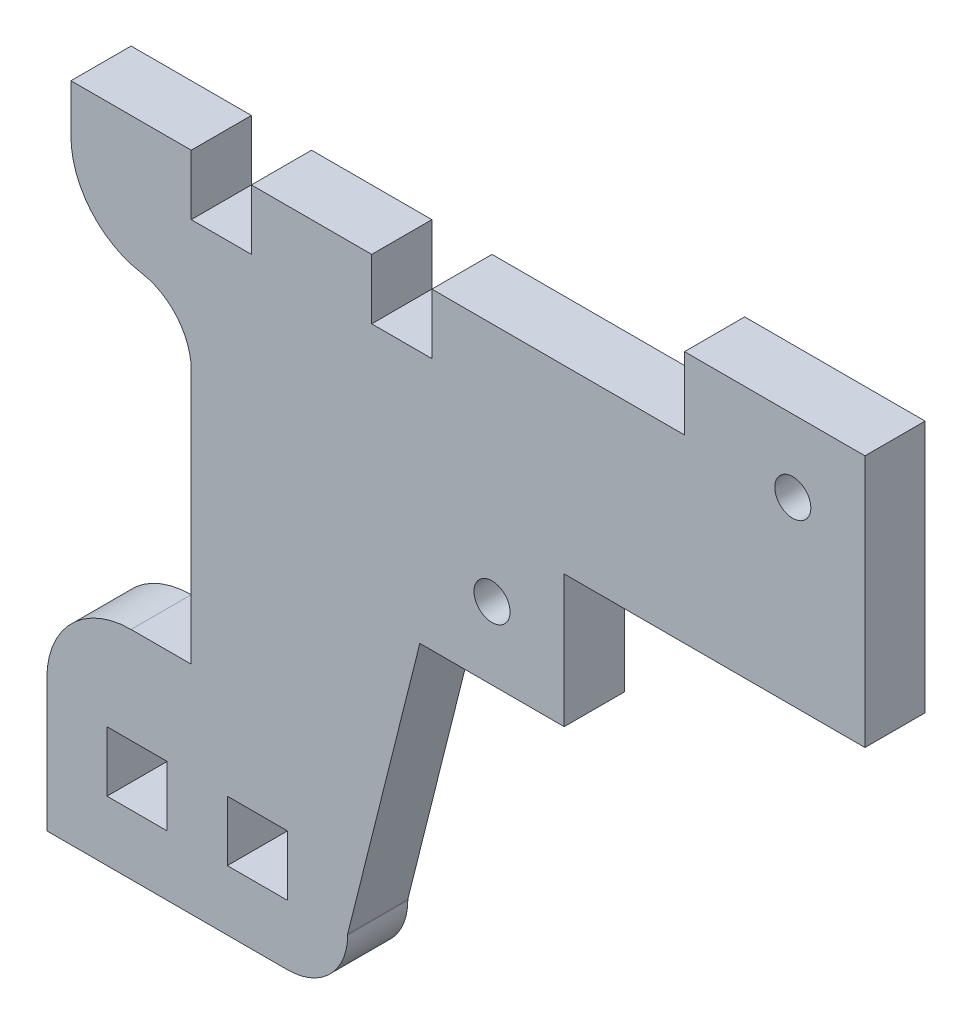
SolidWorks part; units mm, degrees
ref_plane "Plan de face" through (0, 0, 0) normal (0, 0, 1) x (1, 0, 0)
ref_plane "Plan de dessus" through (0, 0, 0) normal (0, 1, 0) x (1, 0, 0)
ref_plane "Plan de droite" through (0, 0, 0) normal (1, 0, 0) x (0, 0, -1)
sketch "Esquisse1" plane through (0, 0, 0) normal (0, 0, 1) x (1, 0, 0)
  line L0 (31, 19) -> (43, 19)
  line L1 (5, 0) -> (10, 0)
  line L2 (0, 0) -> (0, 8)
  line L3 (12, 40) -> (17, 40)
  line L4 (68, 30) -> (68, 51)
  line L5 (27, 40) -> (32, 40)
  line L6 (2, 40) -> (2, 45)
  line L7 (2, 45) -> (12, 45)
  line L8 (12, 40) -> (12, 45)
  line L9 (15, 0) -> (20, 0)
  line L10 (17, 40) -> (17, 45)
  line L11 (17, 45) -> (27, 45)
  line L12 (27, 40) -> (27, 45)
  line L13 (15, 0) -> (15, -5)
  line L14 (10, -5) -> (5, -5)
  line L15 (10, 0) -> (10, -5)
  line L16 (5, 0) -> (5, -5)
  line L18 (0, 0) -> (0, -5.81)
  line L19 (2, 34) -> (2, 40)
  line L20 (0, 8) -> (12, 8)
  line L22 (2, 34) -> (12, 34)
  line L23 (12, 8) -> (12, 34)
  line L24 (20, 0) -> (20, -5)
  line L25 (43, 19) -> (43, 30)
  line L26 (43, 30) -> (68, 30)
  line L27 (53, 45) -> (53, 51)
  line L28 (53, 51) -> (68, 51)
  line L29 (32, 40) -> (32, 45)
  line L30 (31, 19) -> (25, -4.929)
  line L31 (20, -5) -> (15, -5)
  line L32 (25, -4.929) -> (25, -10)
  line L33 (25, -10) -> (0, -10)
  line L34 (0, -5.81) -> (0, -10)
  line L35 (32, 45) -> (53, 45)
  circle A0 centre (62, 45) radius 1.5
  circle A1 centre (37, 25) radius 1.5
  circle A2 centre (37, 25) radius 1.5 construction
  circle A3 centre (62, 45) radius 1.5 construction
  dimension "D9" = 3
  dimension "D11" = 6
  dimension "D14" = 6
  dimension "D12" = 6
  dimension "D3" = 10
  dimension "D4" = 5
  dimension "D5" = 5
  dimension "D6" = 10
  dimension "D7" = 8
  dimension "D8" = 26
  dimension "D10" = 5
  dimension "D13" = 12
  dimension "D16" = 6
  dimension "D17" = 15
  dimension "D18" = 40
  dimension "D19" = 2
  dimension "D20" = 5
  dimension "D21" = 5
  dimension "D22" = 5
  dimension "D23" = 5
  dimension "D24" = 25
extrude "Boss.-Extru.1" add sketch "Esquisse1" along normal blind 5
fillet "Congé1" radius 7 2 edges at (0, 8, 2.5) (2, 34, 2.5)
fillet "Congé2" radius 5 1 edges at (12, 34, 2.5)
fillet "Congé3" radius 5 1 edges at (25, -10, 2.5)
